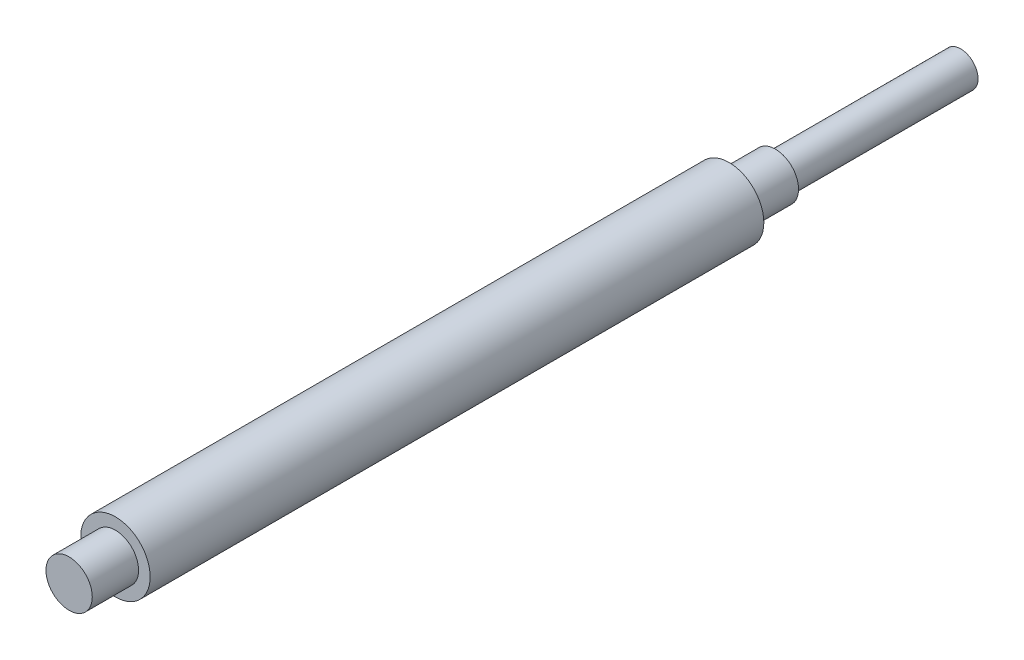
SolidWorks part; units mm, degrees
material "Aço inoxidável (ferrítico)"
ref_plane "Plano frontal" through (0, 0, 0) normal (0, 0, 1) x (1, 0, 0)
ref_plane "Plano superior" through (0, 0, 0) normal (0, 1, 0) x (1, 0, 0)
ref_plane "Plano direito" through (0, 0, 0) normal (1, 0, 0) x (0, 0, -1)
sketch "Esboço1" plane through (0, 0, 0) normal (0, 0, 1) x (1, 0, 0)
  circle A0 centre (0, 0) radius 3
  dimension "D1" = 6
extrude "Ressalto-extrusão1" add sketch "Esboço1" along normal blind 77
sketch "Esboço2" plane through (0, 0, 77) normal (0, 0, 1) x (1, 0, 0)
  circle A0 centre (0, 0) radius 3
  circle A1 centre (0, 0) radius 2
  dimension "D1" = 6
  dimension "D2" = 4
extrude "Corte-extrusão1" cut sketch "Esboço2" against normal blind 4
sketch "Esboço3" plane through (0, 0, 0) normal (0, 0, -1) x (-1, 0, 0)
  circle A0 centre (0, 0) radius 3
  circle A1 centre (0, 0) radius 2
  dimension "D1" = 6
  dimension "D2" = 4
extrude "Corte-extrusão2" cut sketch "Esboço3" against normal offset from surface (20 mm away) 53 up to face at (2, 0, 73)
sketch "Esboço4" plane through (0, 0, 0) normal (0, 0, -1) x (-1, 0, 0)
  circle A0 centre (0, 0) radius 2.5
  circle A1 centre (0, 0) radius 1.5
  dimension "D1" = 5
  dimension "D2" = 3
extrude "Corte-extrusão3" cut sketch "Esboço4" against normal offset from surface (16 mm away) 4 up to face at (3, 0, 20)
